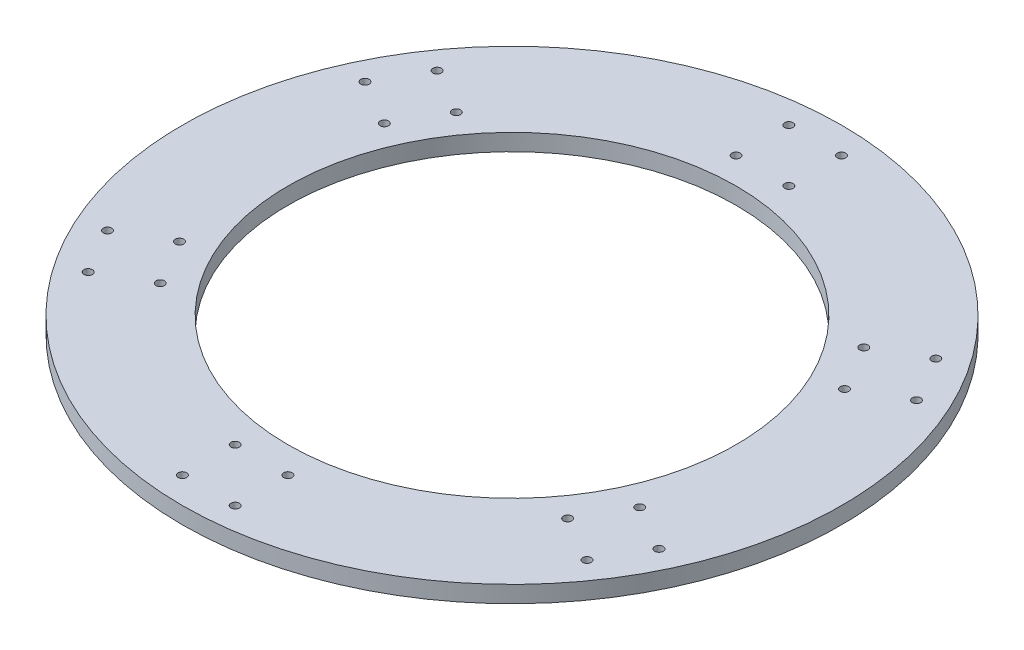
SolidWorks part; units mm, degrees
material "Delrin 2700 NC010, Low Viscosity Acetal Copolymer (SS)"
ref_plane "Front Plane" through (0, 0, 0) normal (0, 0, 1) x (1, 0, 0)
ref_plane "Top Plane" through (0, 0, 0) normal (0, 1, 0) x (1, 0, 0)
ref_plane "Right Plane" through (0, 0, 0) normal (1, 0, 0) x (0, 0, -1)
sketch "Sketch1" plane through (0, 0, 0) normal (0, 1, 0) x (1, 0, 0)
  circle A0 centre (0, 0) radius 125
  dimension "D1" = 250
extrude "Boss-Extrude1" add sketch "Sketch1" along normal blind 6.35
sketch "Sketch2" plane through (0, 0, 0) normal (0, 1, 0) x (1, 0, 0)
  circle A0 centre (0, 0) radius 85
  dimension "D1" = 170
extrude "Cut-Extrude1" cut sketch "Sketch2" along normal through all
hole_wizard "M3 Clearance Hole1" positions "Sketch3" profile "Sketch4" hole size "M3" standard "ANSI Metric" end condition through all
sketch "Sketch3" plane through (0, 0, 0) normal (0, -1, 0) x (-1, 0, 0)
  line L0 (0, 0) -> (0, -125) construction
  line L8 (10, -95) -> (-10, -95) construction
  circle A0 centre (0, 0) radius 125 construction
  point P0 (10, -95)
  point P33 (-10, -95)
  point P38 (10, -115)
  point P41 (-10, -115)
  point P52 (-77.2724, -56.1603)
  point P53 (-87.2724, -38.8397)
  point P54 (-94.5929, -66.1603)
  point P55 (-104.5929, -48.8397)
  point P56 (-87.2724, 38.8397)
  point P57 (-77.2724, 56.1603)
  point P58 (-104.5929, 48.8397)
  point P59 (-94.5929, 66.1603)
  point P60 (0, 0)
  point P61 (-77.2724, -56.1603)
  point P68 (-10, 95)
  point P69 (10, 95)
  point P70 (-10, 115)
  point P71 (10, 115)
  point P72 (77.2724, 56.1603)
  point P73 (87.2724, 38.8397)
  point P74 (94.5929, 66.1603)
  point P75 (104.5929, 48.8397)
  point P76 (87.2724, -38.8397)
  point P77 (77.2724, -56.1603)
  point P78 (104.5929, -48.8397)
  point P79 (94.5929, -66.1603)
  dimension "D3" = 20
  dimension "D4" = 95
  dimension "D5" = 20
  dimension "D6" = 20
  dimension "D7" = 6
sketch "Sketch4" plane through (-10, 0, 95) normal (1, 0, 0) x (0, 0, -1)
  line L0 (0, 0) -> (0, 6.35)
  line L1 (0, 6.35) -> (1.6, 6.35)
  line L2 (1.6, 6.35) -> (1.6, 0)
  line L5 (1.6, 0) -> (0, 0)
  line L11 (0, -6.35) -> (0, 107.95) construction
  dimension "Thru Hole Dia." = 3.2
  dimension "Thru Hole Depth" = 6.35
